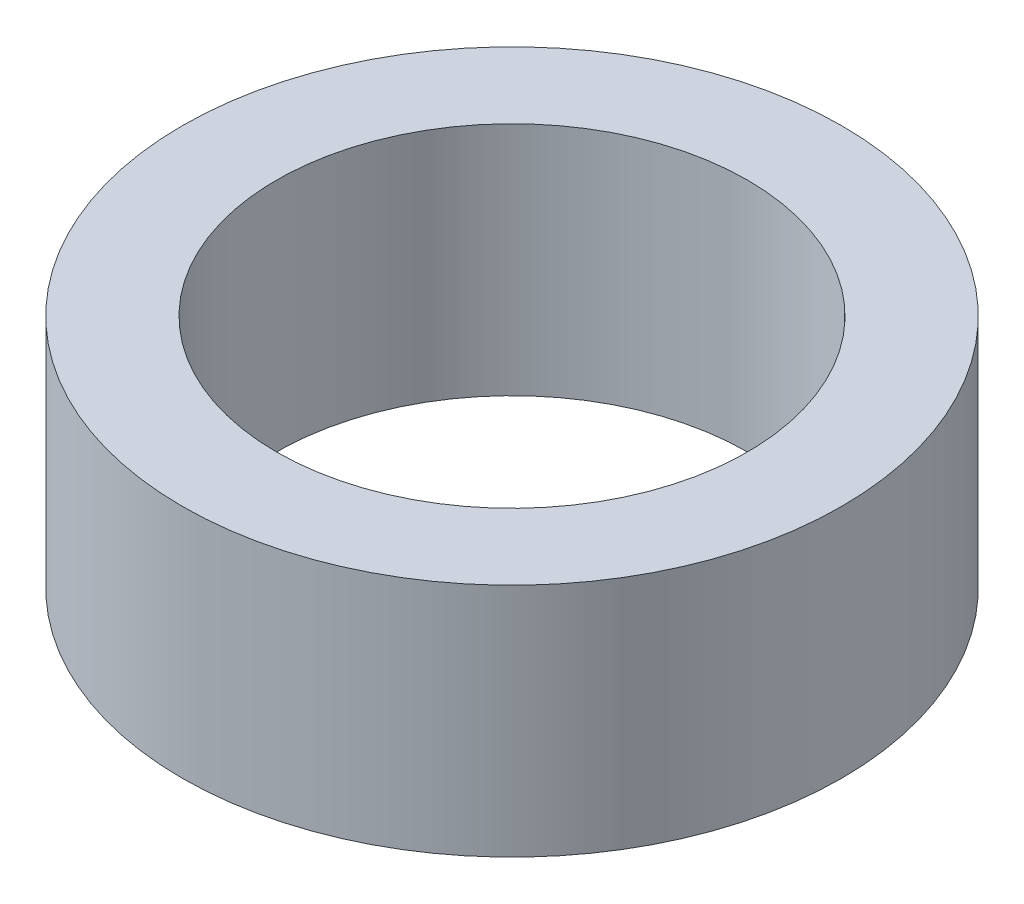
SolidWorks part; units mm, degrees
ref_plane "Front Plane" through (0, 0, 0) normal (0, 0, 1) x (1, 0, 0)
ref_plane "Top Plane" through (0, 0, 0) normal (0, 1, 0) x (1, 0, 0)
ref_plane "Right Plane" through (0, 0, 0) normal (1, 0, 0) x (0, 0, -1)
sketch "Sketch1" plane through (0, 0, 0) normal (0, 1, 0) x (1, 0, 0)
  circle A0 centre (0, 0) radius 5
  circle A1 centre (0, 0) radius 7
  dimension "D1" = 10
  dimension "D2" = 14
extrude "Boss-Extrude1" add sketch "Sketch1" along normal blind 5
